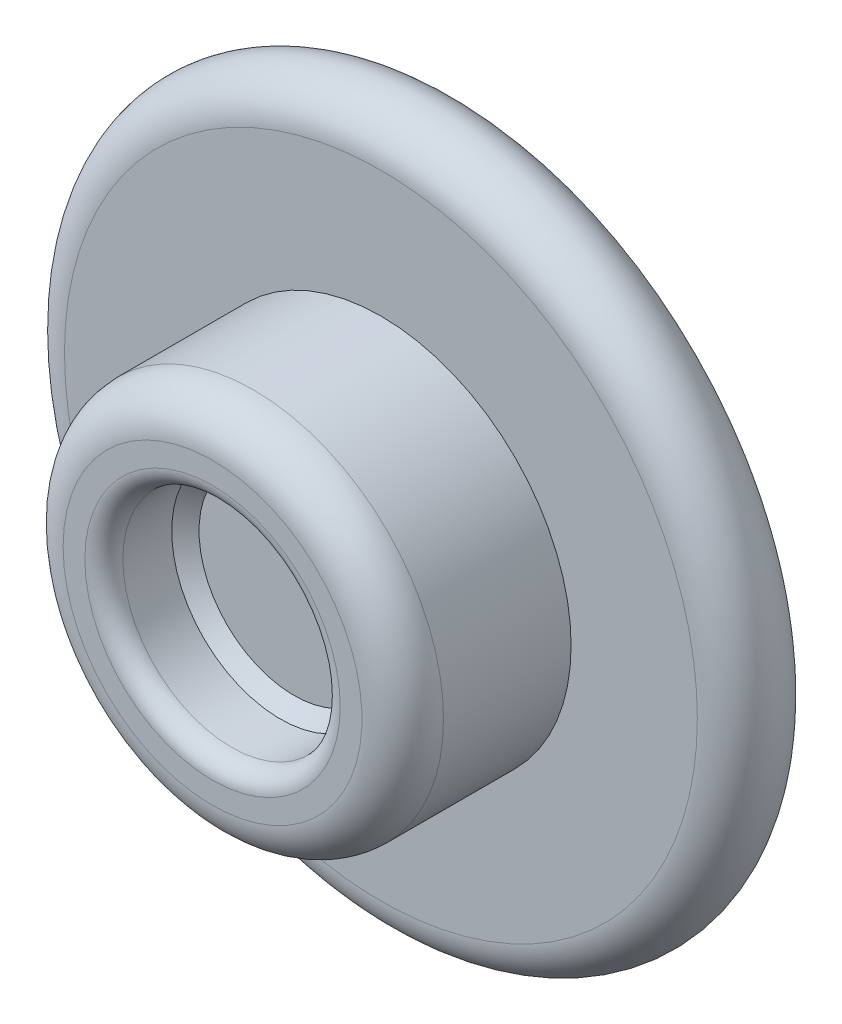
SolidWorks part; units mm, degrees
ref_plane "Alzado" through (0, 0, 0) normal (0, 0, 1) x (1, 0, 0)
ref_plane "Planta" through (0, 0, 0) normal (0, 1, 0) x (1, 0, 0)
ref_plane "Vista lateral" through (0, 0, 0) normal (1, 0, 0) x (0, 0, -1)
sketch "Croquis1" plane through (0, 0, 0) normal (1, 0, 0) x (0, 0, -1)
  line L0 (-43.4213, 0) -> (43.4213, 0) construction
  line L2 (0, -38.4861) -> (0, 38.4861) construction
  line L3 (0, 15.5462) -> (3, 15.5462) construction
  line L4 (0, 35.5462) -> (4, 35.5462) construction
  line L5 (4, 35.5462) -> (4, 18) construction
  line L6 (4, 18) -> (14.1961, 18) construction
  line L7 (14.1961, 18) -> (14.1961, 7) construction
  line L8 (3, 11) -> (9, 11) construction
  line L9 (10.5, 9.5) -> (10.5, 4) construction
  line L10 (10.5, 4) -> (12.998, 4)
  line L12 (12.998, 4) -> (13.5, 3.498)
  line L13 (13.5, 3.498) -> (13.5, 0)
  line L25 (3, 15.5462) -> (3, 11) construction
  line L26 (0, 15.5462) -> (0, 35.5462) construction
  line L27 (13.5, 0) -> (25.5, 0) construction
  line L29 (10.5, 9.5) -> (10.5, 8) construction
  line L31 (10.5, 8) -> (12, 8) construction
  line L32 (12, 8) -> (14.1961, 18) construction
  line L33 (10.5, 7) -> (10.5, 4)
  line L34 (10.5, 7) -> (16.6961, 7)
  line L37 (13.5, 0) -> (25.5, 0)
  line L38 (16.6961, 7) -> (16.6961, 17)
  line L39 (16.6961, 17) -> (24.1899, 4.676)
  arc A0 (24.1899, 4.676) -> (25.5, 0) centre (16.5, 0) cw
  arc A1 (9, 11) -> (10.5, 9.5) centre (9, 9.5) cw construction
  point P3 (0, 0)
  point P6 (0, 0)
  point P28 (13.5, 0)
  point P32 (3, 13.2731)
  dimension "D5" = 4
  dimension "D11" = 9
  dimension "D4" = 18
  dimension "D2" = 11
  dimension "D3" = 20
  dimension "D6" = 4
  dimension "D7" = 10.1961
  dimension "D8" = 11
  dimension "D9" = 3
  dimension "D10" = 2.5
  dimension "D12" = 7.5
  dimension "D13" = 6
  dimension "D14" = 13.5
  dimension "D15" = 45
  dimension "D16" = 8
  dimension "D17" = 0.71
  dimension "D18" = 1.5
  dimension "D19" = 35.5462
  dimension "D20" = 3
  dimension "D21" = 3
  dimension "D22" = 1
  dimension "D23" = 31.303
revolve "Revolución1" add sketch "Croquis1" angle 360 about L0
fillet "Redondeo3" radius 0.7 1 edges at (4, 0, -10.5)
fillet "Redondeo5" radius 1.5 2 edges at (7, 0, -10.5) (17, 0, -16.6961)
ref_plane "Plano1" through (0, 0, -25.5) normal (0, 0, -1) x (-1, 0, 0)
sketch "Croquis2" plane through (0, 0, -25.5) normal (0, 0, -1) x (-1, 0, 0)
  line L0 (4.676, 0) -> (-4.676, 0) construction
  line L5 (-0.35, 2.6772) -> (0.5573, 4.1148)
  line L8 (0.5573, 4.1148) -> (-0.216, 3.6772)
  line L9 (-0.216, 3.6772) -> (1.0137, 5.2072)
  line L10 (1.0137, 5.2072) -> (0.4203, 4.2671)
  line L11 (0.4203, 4.2671) -> (0.85, 4.5102)
  line L12 (0.85, 4.5102) -> (0.35, 2.6772)
  line L13 (4.5102, -0.85) -> (2.6772, -0.35)
  line L26 (2.6772, 0.35) -> (4.1148, -0.5573)
  line L27 (4.1148, -0.5573) -> (3.6772, 0.216)
  line L28 (3.6772, 0.216) -> (5.2072, -1.0137)
  line L29 (5.2072, -1.0137) -> (4.2671, -0.4203)
  line L30 (4.2671, -0.4203) -> (4.5102, -0.85)
  line L31 (-0.85, -4.5102) -> (-0.35, -2.6772)
  line L32 (0.35, -2.6772) -> (-0.5573, -4.1148)
  line L33 (-0.5573, -4.1148) -> (0.216, -3.6772)
  line L34 (0.216, -3.6772) -> (-1.0137, -5.2072)
  line L35 (-1.0137, -5.2072) -> (-0.4203, -4.2671)
  line L36 (-0.4203, -4.2671) -> (-0.85, -4.5102)
  line L37 (-4.5102, 0.85) -> (-2.6772, 0.35)
  line L38 (-2.6772, -0.35) -> (-4.1148, 0.5573)
  line L39 (-4.1148, 0.5573) -> (-3.6772, -0.216)
  line L40 (-3.6772, -0.216) -> (-5.2072, 1.0137)
  line L41 (-5.2072, 1.0137) -> (-4.2671, 0.4203)
  line L42 (-4.2671, 0.4203) -> (-4.5102, 0.85)
  circle A0 centre (0, 0) radius 4.676 construction
  circle A3 centre (0, 0) radius 1.5
  circle A4 centre (0, 0) radius 2.5
  arc A5 (0.35, 2.6772) -> (-0.35, 2.6772) centre (0, 0) ccw
  circle A6 centre (0, 0) radius 2.7 construction
  arc A8 (2.6772, -0.35) -> (2.6772, 0.35) centre (0, 0) ccw
  arc A9 (-0.35, -2.6772) -> (0.35, -2.6772) centre (0, 0) ccw
  arc A10 (-2.6772, 0.35) -> (-2.6772, -0.35) centre (0, 0) ccw
  point P1 (0, 2.7)
  point P2 (0, 0)
  point P6 (0, 0)
  point P16 (0, 0)
  point P44 (0, 0)
  dimension "D2" = 3
  dimension "D3" = 1
  dimension "D5" = 0.2
  dimension "D6" = 1.9
  dimension "D7" = 1.7
  dimension "D8" = 0.7
  dimension "D9" = 0.5
  dimension "D10" = 1
  dimension "D11" = 2.53
  dimension "D12" = 0.566
  dimension "D14" = 0.6637
  dimension "D4" = 0.2
  dimension "D13" = 4
extrude "Cortar-Extruir1" cut sketch "Croquis2" against normal blind 3
ref_plane "Plano2" through (0, 0, -23.77) normal (0, 0, 1) x (1, 0, 0)
sketch "Croquis3" plane through (0, 0, -23.77) normal (0, 0, 1) x (1, 0, 0)
  line L0 (12.4254, 0) -> (-12.4254, 0) construction
  line L1 (-0.35, 6.6668) -> (0.5573, 8.1044)
  line L2 (0.5573, 8.1044) -> (-0.216, 7.6668)
  line L3 (-0.216, 7.6668) -> (1.0137, 9.1968)
  line L4 (1.0137, 9.1968) -> (0.4203, 8.2567)
  line L5 (0.4203, 8.2567) -> (0.85, 8.4999)
  line L6 (0.85, 8.4999) -> (0.35, 6.6668)
  line L7 (3.6355, 5.5993) -> (5.2146, 6.229)
  line L8 (5.2146, 6.229) -> (4.3317, 6.3296)
  line L9 (4.3317, 6.3296) -> (6.2258, 6.8446)
  line L10 (6.2258, 6.8446) -> (5.1932, 6.4328)
  line L11 (5.1932, 6.4328) -> (5.6838, 6.3769)
  line L12 (5.6838, 6.3769) -> (4.2018, 5.1879)
  line L13 (6.2324, 2.393) -> (7.88, 1.9744)
  line L20 (7.88, 1.9744) -> (7.2248, 2.5746)
  line L21 (7.2248, 2.5746) -> (9.0599, 1.8779)
  line L22 (9.0599, 1.8779) -> (7.9825, 2.1517)
  line L23 (7.9825, 2.1517) -> (8.3465, 1.8182)
  line L24 (8.3465, 1.8182) -> (6.4487, 1.7273)
  line L25 (6.4487, -1.7273) -> (7.5356, -3.0345)
  line L26 (7.5356, -3.0345) -> (7.3583, -2.1637)
  line L27 (7.3583, -2.1637) -> (8.4335, -3.806)
  line L28 (8.4335, -3.806) -> (7.7227, -2.9512)
  line L29 (7.7227, -2.9512) -> (7.8212, -3.435)
  line L30 (7.8212, -3.435) -> (6.2324, -2.393)
  line L31 (4.2018, -5.1879) -> (4.3128, -6.8842)
  line L32 (4.3128, -6.8842) -> (4.6812, -6.0756)
  line L33 (4.6812, -6.0756) -> (4.5857, -8.0362)
  line L34 (4.5857, -8.0362) -> (4.5131, -6.9269)
  line L35 (4.5131, -6.9269) -> (4.3084, -7.3761)
  line L36 (4.3084, -7.3761) -> (3.6355, -5.5993)
  line L37 (0.35, -6.6668) -> (-0.5573, -8.1044)
  line L38 (-0.5573, -8.1044) -> (0.216, -7.6668)
  line L39 (0.216, -7.6668) -> (-1.0137, -9.1968)
  line L40 (-1.0137, -9.1968) -> (-0.4203, -8.2567)
  line L41 (-0.4203, -8.2567) -> (-0.85, -8.4999)
  line L42 (-0.85, -8.4999) -> (-0.35, -6.6668)
  line L43 (-3.6355, -5.5993) -> (-5.2146, -6.229)
  line L44 (-5.2146, -6.229) -> (-4.3317, -6.3296)
  line L45 (-4.3317, -6.3296) -> (-6.2258, -6.8446)
  line L46 (-6.2258, -6.8446) -> (-5.1932, -6.4328)
  line L47 (-5.1932, -6.4328) -> (-5.6838, -6.3769)
  line L48 (-5.6838, -6.3769) -> (-4.2018, -5.1879)
  line L49 (-6.2324, -2.393) -> (-7.88, -1.9744)
  line L50 (-7.88, -1.9744) -> (-7.2248, -2.5746)
  line L51 (-7.2248, -2.5746) -> (-9.0599, -1.8779)
  line L52 (-9.0599, -1.8779) -> (-7.9825, -2.1517)
  line L53 (-7.9825, -2.1517) -> (-8.3465, -1.8182)
  line L54 (-8.3465, -1.8182) -> (-6.4487, -1.7273)
  line L55 (-6.4487, 1.7273) -> (-7.5356, 3.0345)
  line L56 (-7.5356, 3.0345) -> (-7.3583, 2.1637)
  line L57 (-7.3583, 2.1637) -> (-8.4335, 3.806)
  line L58 (-8.4335, 3.806) -> (-7.7227, 2.9512)
  line L59 (-7.7227, 2.9512) -> (-7.8212, 3.435)
  line L60 (-7.8212, 3.435) -> (-6.2324, 2.393)
  line L61 (-4.2018, 5.1879) -> (-4.3128, 6.8842)
  line L62 (-4.3128, 6.8842) -> (-4.6812, 6.0756)
  line L63 (-4.6812, 6.0756) -> (-4.5857, 8.0362)
  line L64 (-4.5857, 8.0362) -> (-4.5131, 6.9269)
  line L65 (-4.5131, 6.9269) -> (-4.3084, 7.3761)
  line L66 (-4.3084, 7.3761) -> (-3.6355, 5.5993)
  circle A0 centre (0, 0) radius 1.5 construction
  circle A1 centre (0, 0) radius 4.676 construction
  arc A2 (0.35, 6.6668) -> (-0.35, 6.6668) centre (0, 0) ccw
  circle A4 centre (0, 0) radius 4.676 construction
  circle A5 centre (0, 0) radius 12.4254 construction
  arc A6 (4.2018, 5.1879) -> (3.6355, 5.5993) centre (0, 0) ccw
  arc A7 (6.4487, 1.7273) -> (6.2324, 2.393) centre (0, 0) ccw
  arc A8 (6.2324, -2.393) -> (6.4487, -1.7273) centre (0, 0) ccw
  arc A9 (3.6355, -5.5993) -> (4.2018, -5.1879) centre (0, 0) ccw
  arc A10 (-0.35, -6.6668) -> (0.35, -6.6668) centre (0, 0) ccw
  arc A11 (-4.2018, -5.1879) -> (-3.6355, -5.5993) centre (0, 0) ccw
  arc A12 (-6.4487, -1.7273) -> (-6.2324, -2.393) centre (0, 0) ccw
  arc A13 (-6.2324, 2.393) -> (-6.4487, 1.7273) centre (0, 0) ccw
  arc A14 (-3.6355, 5.5993) -> (-4.2018, 5.1879) centre (0, 0) ccw
  point P1 (0, 4.676)
  point P5 (0, 0)
  point P14 (0, 0)
  point P39 (0, 6.676)
  point P88 (0, 0)
  dimension "D1" = 3
  dimension "D2" = 17
  dimension "D3" = 0.2
  dimension "D4" = 1.9
  dimension "D5" = 1.7
  dimension "D6" = 0.7
  dimension "D7" = 0.5
  dimension "D8" = 1
  dimension "D9" = 2.53
  dimension "D10" = 1.3637
  dimension "D11" = 2
  dimension "D12" = 10
extrude "Cortar-Extruir3" cut sketch "Croquis3" along normal blind 3
